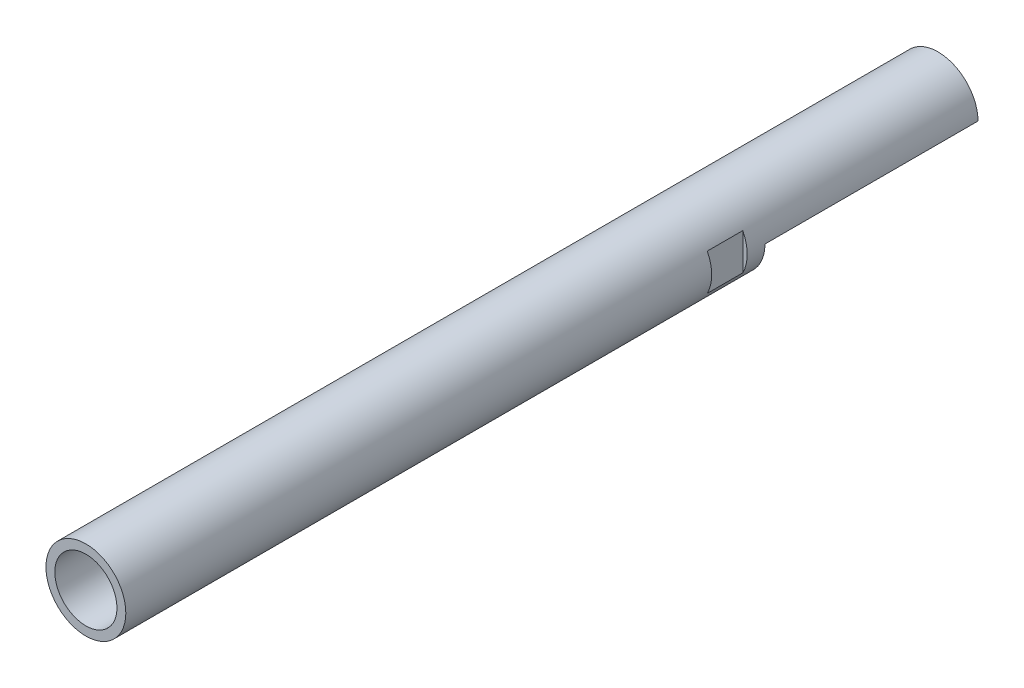
SolidWorks part; units mm, degrees
ref_plane "Front" through (0, 0, 0) normal (0, 0, 1) x (1, 0, 0)
ref_plane "Top" through (0, 0, 0) normal (0, 1, 0) x (1, 0, 0)
ref_plane "Right" through (0, 0, 0) normal (1, 0, 0) x (0, 0, -1)
sketch "Sketch1" plane through (0, 0, 0) normal (0, 0, 1) x (1, 0, 0)
  circle A0 centre (0, 0) radius 9.525
  circle A1 centre (0, 0) radius 14.2875
  dimension "D1" = 19.05
  dimension "D2" = 28.575
extrude "Boss-Extrude1" add sketch "Sketch1" along normal blind 304.8
sketch "Sketch2" plane through (0, 0, 304.8) normal (0, 0, 1) x (1, 0, 0)
  circle A0 centre (0, 0) radius 11.1125
  dimension "D1" = 22.225
extrude "Cut-Extrude1" cut sketch "Sketch2" against normal blind 19.05
sketch "Sketch6" plane through (0, 0, 0) normal (0, 0, -1) x (-1, 0, 0)
  line L0 (14.2875, 0) -> (-14.2875, 0)
  circle A0 centre (0, 0) radius 14.2875 construction
  circle A2 centre (0, 0) radius 14.2875
  arc A3 (-14.2875, 0) -> (14.2875, 0) centre (0, 0) ccw
  dimension "D1" = 0
extrude "Cut-Extrude4" cut sketch "Sketch6" against normal blind 76.2
ref_plane "Plane1" through (0, 0, 82.55) normal (0, 0, -1) x (-1, 0, 0)
sketch "Sketch8" plane through (0, 0, 82.55) normal (0, 0, -1) x (-1, 0, 0)
  line L1 (12.7, 12.7) -> (-12.7, 12.7)
  line L2 (12.7, 12.7) -> (12.7, -12.7)
  line L3 (12.7, -12.7) -> (-12.7, -12.7)
  line L4 (-12.7, 12.7) -> (-12.7, -12.7)
  line L5 (12.7, 12.7) -> (-12.7, -12.7) construction
  line L6 (12.7, -12.7) -> (-12.7, 12.7) construction
  circle A1 centre (0, 0) radius 14.2875
  circle A2 centre (0, 0) radius 14.2875
  dimension "D2" = 25.4
  dimension "D1" = 0
extrude "Cut-Extrude7" cut sketch "Sketch8" against normal blind 12.7 contours L3 A2 | L4 A2
sketch "Sketch9" plane through (0, -12.7, 0) normal (0, -1, 0) x (1, 0, 0)
  line L0 (0, 95.25) -> (0, 304.8) construction
  line L1 (-6.5454, 95.25) -> (6.5454, 95.25) construction
  line L2 (14.2875, 304.8) -> (-14.2875, 304.8) construction
  line L3 (-6.5454, 95.25) -> (6.5454, 95.25) construction
  circle A0 centre (0, 107.95) radius 3.175
  circle A1 centre (0, 171.45) radius 3.175
  dimension "D1" = 76.2
  dimension "D2" = 12.7
  dimension "D3" = 6.35
extrude "Cut-Extrude8" cut sketch "Sketch9" against normal up to next and the other way up to next contours A1 L0 | L0 A1
sketch "Sketch10" plane through (0, 0, 0) normal (0, 0, -1) x (-1, 0, 0)
  line L2 (-14.2875, 0) -> (-9.525, 0)
  line L3 (9.525, 0) -> (14.2875, 0)
  line L4 (-14.2875, 0) -> (-9.525, 0)
  line L5 (9.525, 0) -> (14.2875, 0)
  arc A2 (14.2875, 0) -> (-14.2875, 0) centre (0, 0) ccw
  arc A3 (9.525, 0) -> (-9.525, 0) centre (0, 0) ccw
  arc A4 (14.2875, 0) -> (-14.2875, 0) centre (0, 0) ccw
  arc A5 (9.525, 0) -> (-9.525, 0) centre (0, 0) ccw
  dimension "D1" = 0
